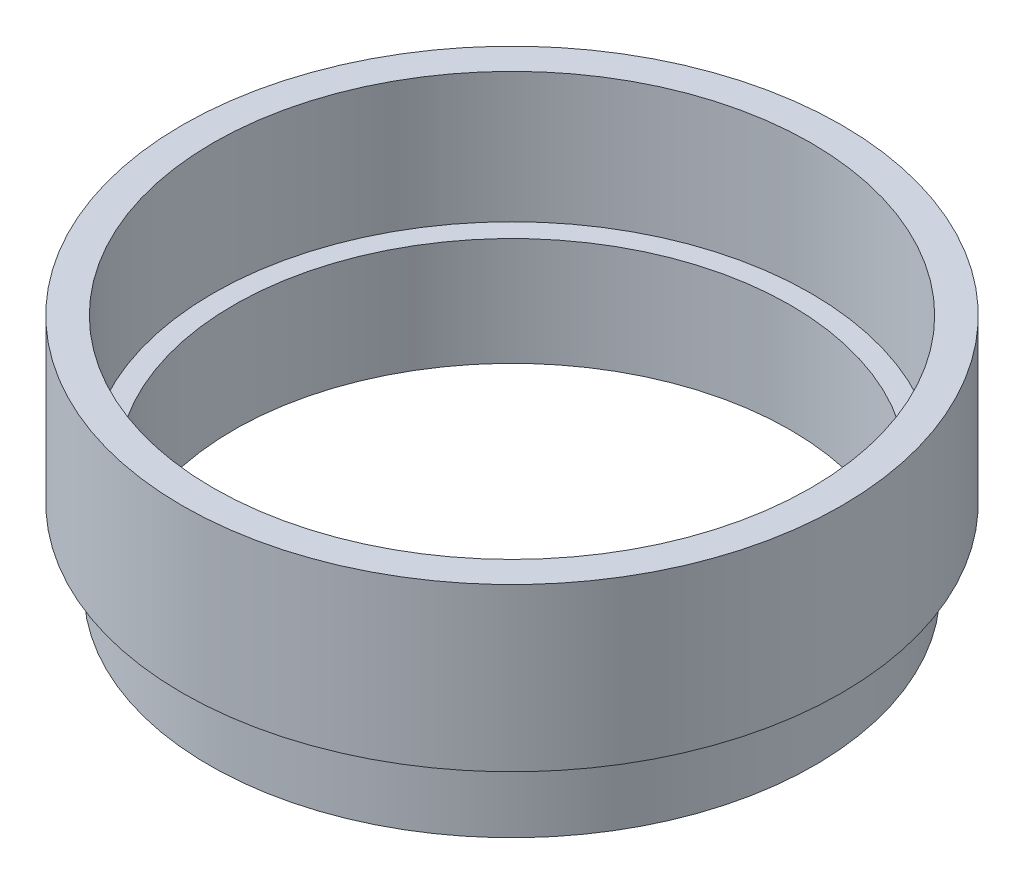
SolidWorks part; units mm, degrees
ref_plane "Front Plane" through (0, 0, 0) normal (0, 0, 1) x (1, 0, 0)
ref_plane "Top Plane" through (0, 0, 0) normal (0, 1, 0) x (1, 0, 0)
ref_plane "Right Plane" through (0, 0, 0) normal (1, 0, 0) x (0, 0, -1)
sketch "Sketch1" plane through (0, 0, 0) normal (0, 0, 1) x (1, 0, 0)
  line L0 (0, 0) -> (0, 6.0593) construction
  line L1 (-13.081, 0) -> (-14.224, 0)
  line L2 (-14.224, 0) -> (-14.224, 3.5814)
  line L3 (-14.224, 3.5814) -> (-15.494, 3.5814)
  line L4 (-15.494, 3.5814) -> (-15.494, 11.2014)
  line L5 (-15.494, 11.2014) -> (-14.0462, 11.2014)
  line L6 (-14.0462, 11.2014) -> (-14.0462, 5.08)
  line L7 (-13.081, 5.08) -> (-13.081, 0)
  line L8 (-13.081, 5.08) -> (-14.0462, 5.08)
  dimension "D1" = 15.494
  dimension "D2" = 7.62
  dimension "D3" = 11.2014
  dimension "D4" = 14.224
  dimension "D5" = 13.081
  dimension "D6" = 1.4478
  dimension "D7" = 5.08
revolve "Revolve1" add sketch "Sketch1" angle 360 about L0
